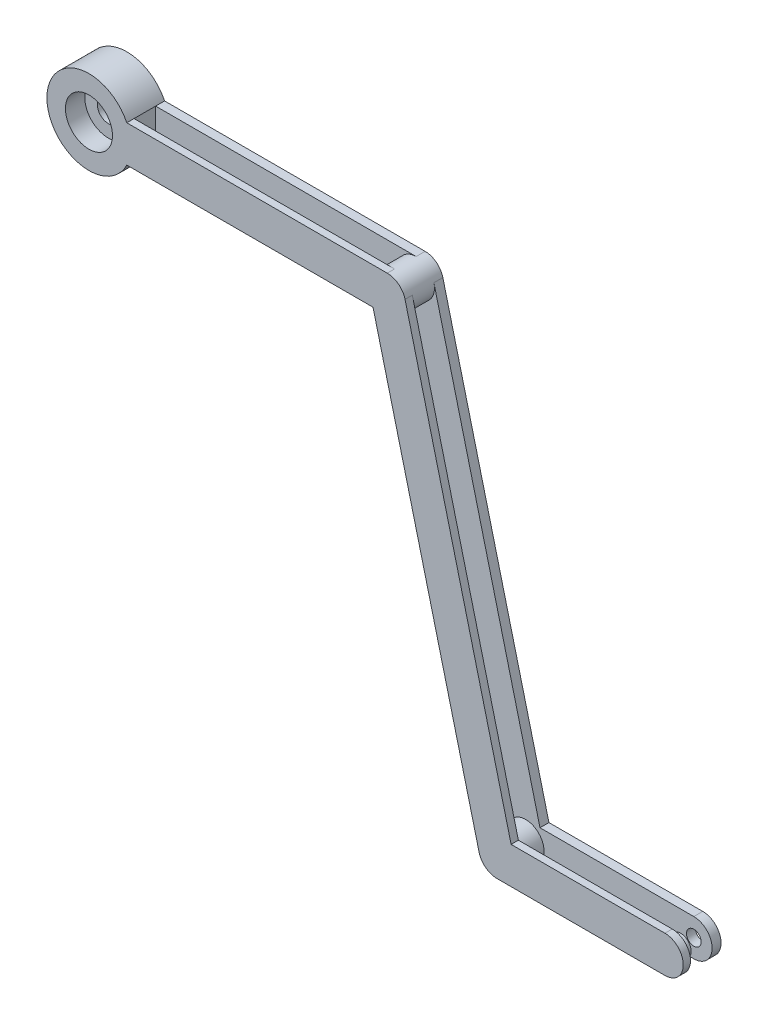
SolidWorks part; units mm, degrees
ref_plane "前视基准面" through (0, 0, 0) normal (0, 0, 1) x (1, 0, 0)
ref_plane "上视基准面" through (0, 0, 0) normal (0, 1, 0) x (1, 0, 0)
ref_plane "右视基准面" through (0, 0, 0) normal (1, 0, 0) x (0, 0, -1)
other "Configuration Table"
sketch "草图1" plane through (0, 0, 0) normal (0, 0, 1) x (1, 0, 0)
  line L0 (0, 0) -> (71, 0) construction
  line L1 (9, 4.3589) -> (71, 4.3589)
  line L2 (9, -4.3589) -> (67.6073, -4.3589)
  line L3 (72.4841, -5.8611) -> (97.081, -103) construction
  line L4 (75.2255, 1.07) -> (100.4737, -98.6411)
  line L5 (67.6073, -4.3589) -> (92.8554, -104.07)
  line L6 (97.081, -103) -> (137.081, -103) construction
  line L7 (100.4737, -98.6411) -> (137.081, -98.6411)
  line L8 (97.081, -107.3589) -> (137.081, -107.3589)
  line L9 (9, -4.3589) -> (9, 4.3589) construction
  arc A0 (9, 4.3589) -> (9, -4.3589) centre (0, 0) ccw
  arc A2 (75.2255, 1.07) -> (71, 4.3589) centre (71, 0) ccw
  arc A3 (75.2255, 1.07) -> (71, 4.3589) centre (71, 0) ccw
  arc A4 (92.8554, -104.07) -> (97.081, -107.3589) centre (97.081, -103) ccw
  arc A6 (137.081, -107.3589) -> (137.081, -98.6411) centre (137.081, -103) ccw
  arc A8 (92.8554, -104.07) -> (97.081, -107.3589) centre (97.081, -103) ccw
  point P4 (35.5, 0)
  point P11 (84.0405, -51.5)
  point P18 (117.081, -103)
  point P25 (0, 0)
  dimension "D1" = 20
  dimension "D2" = 9
  dimension "D3" = 71
  dimension "D4" = 103
  dimension "D5" = 40
extrude "凸台-拉伸1" add sketch "草图1" along normal blind 9 contours L8 A6 L7 L4 A2 L1 A0 L2 L5 A4
sketch "草图2" plane through (0, 0, 0) normal (0, 0, -1) x (-1, 0, 0)
  circle A0 centre (0, 0) radius 5.6
  dimension "D1" = 11.2
extrude "切除-拉伸1" cut sketch "草图2" against normal blind 4.6
sketch "草图3" plane through (0, 0, 9) normal (0, 0, 1) x (1, 0, 0)
  circle A0 centre (0, 0) radius 2.6
  dimension "D1" = 5.2
extrude "切除-拉伸2" cut sketch "草图3" against normal through all
sketch "草图5" plane through (0, 4.3589, 0) normal (0, 1, 0) x (1, 0, 0)
  line L0 (9, -1.7299) -> (9, -6.8696)
  line L1 (9, -9) -> (9, 0) construction
  line L2 (9, -6.8696) -> (141.4399, -6.8696)
  line L3 (141.4399, -9) -> (141.4399, 0) construction
  line L4 (141.4399, -6.8696) -> (141.4399, -1.7299)
  line L5 (141.4399, -1.7299) -> (9, -1.7299)
extrude "切除-拉伸3" cut sketch "草图5" against normal through all
sketch "草图6" plane through (0, 0, 9) normal (0, 0, 1) x (1, 0, 0)
  circle A0 centre (97.179, -102.8741) radius 4.4859
  circle A1 centre (71, 0) radius 4.3589
extrude "凸台-拉伸2" add sketch "草图6" against normal up to surface (7.2701 mm away) contours A1 up to face at (80.0764, -51.5, 1.7299)
sketch "草图7" plane through (0, 0, 9) normal (0, 0, 1) x (1, 0, 0)
  circle A0 centre (97.081, -103) radius 4.3589
extrude "凸台-拉伸3" add sketch "草图7" against normal up to surface (7.2701 mm away) up to face at (79.5409, -52.188, 1.7299)
sketch "草图8" plane through (0, 0, 1.7299) normal (0, 0, 1) x (1, 0, 0)
  circle A0 centre (137.081, -103) radius 2.5
  dimension "D1" = 5
extrude "凸台-拉伸4" add sketch "草图8" along normal blind 2
sketch "草图9" plane through (0, 0, 9) normal (0, 0, 1) x (1, 0, 0)
  circle A0 centre (137.081, -103) radius 1.75
  dimension "D1" = 3.5
extrude "切除-拉伸4" cut sketch "草图9" against normal up to next
mirror "镜向8" about plane through (0, 0, 0) normal (0, 0, 1) of bodies 113
sketch "草图12" plane through (0, 4.3589, 0) normal (0, 1, 0) x (1, 0, 0)
  line L0 (-10, 0) -> (141.4399, 0)
  line L1 (-10, 9) -> (-10, -9) construction
  line L2 (141.4399, -1.7299) -> (141.4399, 1.7299) construction
  line L3 (141.4399, 0) -> (141.4399, -9)
  line L4 (141.4399, -9) -> (-10, -9)
  line L5 (-10, -9) -> (9, -9) construction
  line L6 (-10, -9) -> (-10, 0)
extrude "切除-拉伸5" cut sketch "草图12" against normal through all both and the other way through all
